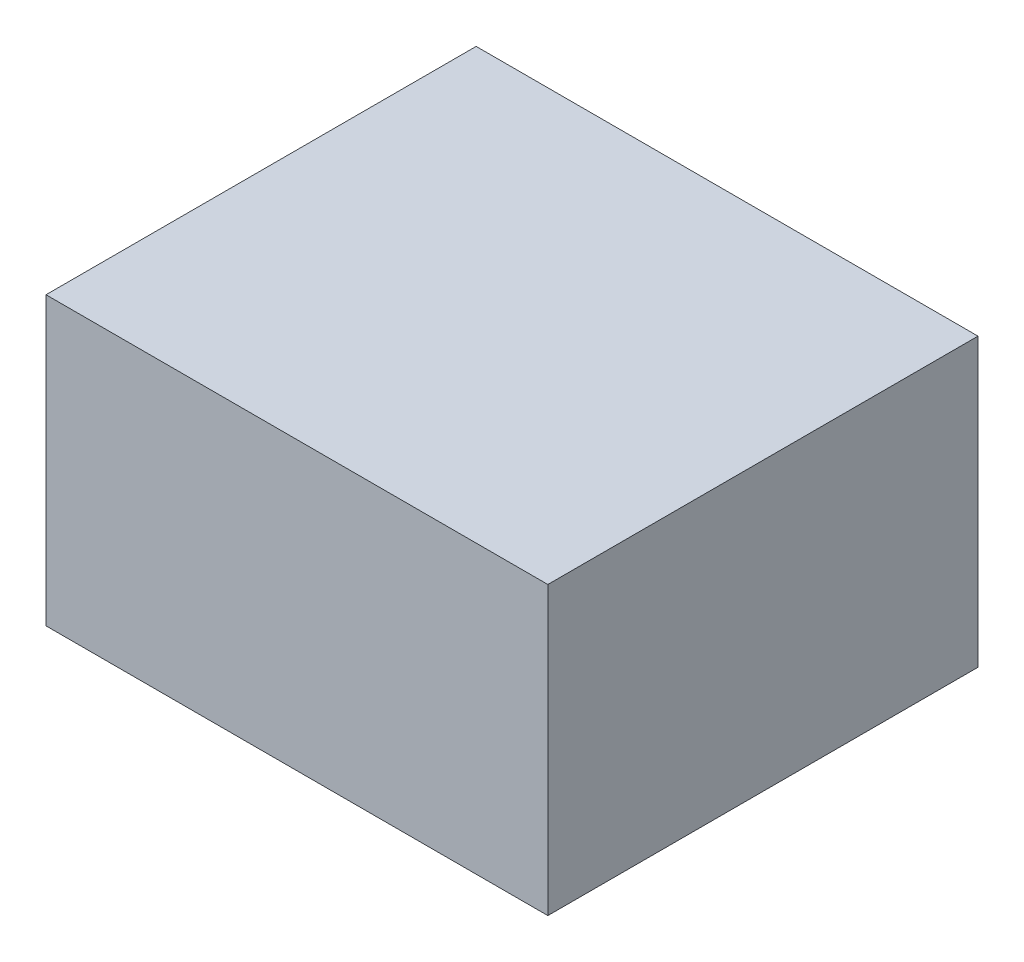
SolidWorks part; units mm, degrees
ref_plane "Front Plane" through (0, 0, 0) normal (0, 0, 1) x (1, 0, 0)
ref_plane "Top Plane" through (0, 0, 0) normal (0, 1, 0) x (1, 0, 0)
ref_plane "Right Plane" through (0, 0, 0) normal (1, 0, 0) x (0, 0, -1)
sketch "SK_P01_Spliceblock" plane through (0, 0, 0) normal (0, 1, 0) x (1, 0, 0)
  line L0 (-7, -6) -> (7, -6)
  line L1 (7, -6) -> (7, 6)
  line L2 (7, 6) -> (-7, 6)
  line L3 (-7, 6) -> (-7, -6)
extrude "P01_Spliceblock" add sketch "SK_P01_Spliceblock" along normal blind 8
